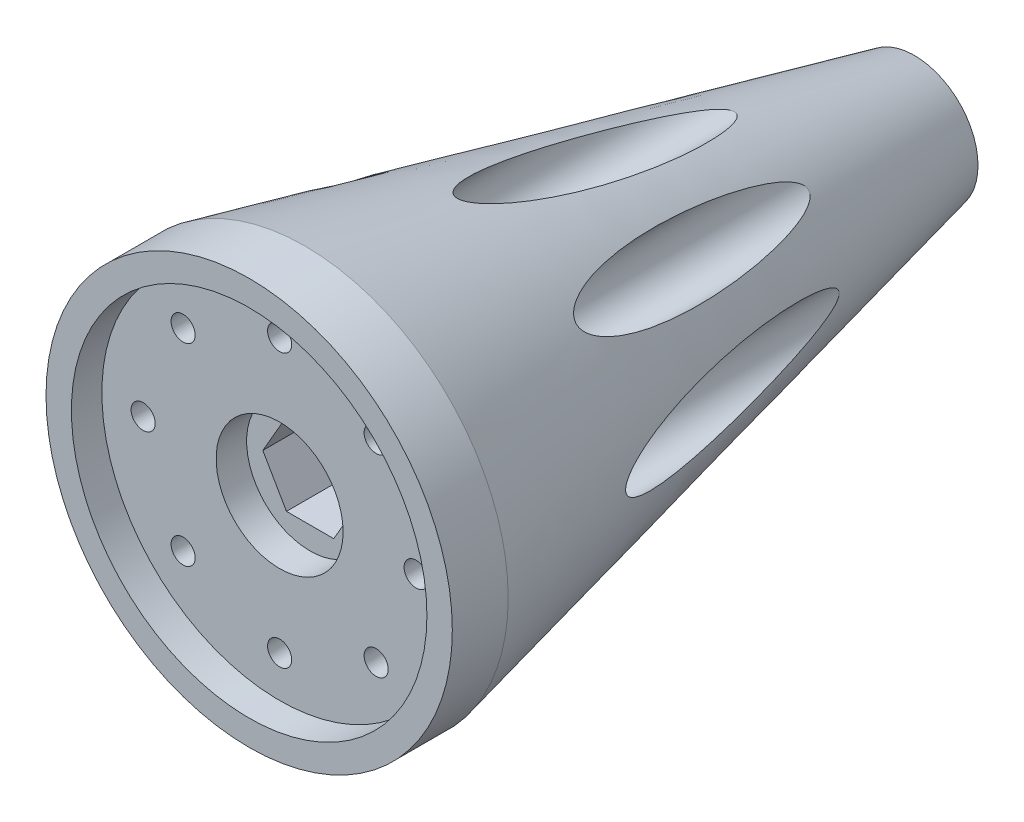
SolidWorks part; units mm, degrees
ref_plane "Front Plane" through (0, 0, 0) normal (0, 0, 1) x (1, 0, 0)
ref_plane "Top Plane" through (0, 0, 0) normal (0, 1, 0) x (1, 0, 0)
ref_plane "Right Plane" through (0, 0, 0) normal (1, 0, 0) x (0, 0, -1)
sketch "Sketch2" plane through (0, 0, 0) normal (1, 0, 0) x (0, 0, -1)
  line L0 (0, 0) -> (28.0138, 0) construction
  line L1 (0, 14) -> (2.4, 14)
  line L2 (2.4, 14) -> (2.4, 0)
  line L3 (2.4, 0) -> (52.4, 0)
  line L4 (52.4, 0) -> (52.4, 5)
  line L5 (52.4, 5) -> (4.4, 16)
  line L6 (4.4, 16) -> (0, 16)
  line L7 (0, 16) -> (0, 14)
  dimension "D1" = 28
  dimension "D2" = 2.4
  dimension "D3" = 2
  dimension "D4" = 2
  dimension "D5" = 10
  dimension "D6" = 50
revolve "Revolve1" add sketch "Sketch2" angle 360 about L0
sketch "Sketch3" plane through (0, 0, 0) normal (0, 0, 1) x (1, 0, 0)
  line L1 (3.7239, 0) -> (1.862, 3.225)
  line L2 (1.862, 3.225) -> (-1.862, 3.225)
  line L3 (-1.862, 3.225) -> (-3.7239, 0)
  line L4 (-3.7239, 0) -> (-1.862, -3.225)
  line L5 (-1.862, -3.225) -> (1.862, -3.225)
  line L6 (1.862, -3.225) -> (3.7239, 0)
  circle A0 centre (0, 0) radius 3.225 construction
  dimension "D1" = 6.45
extrude "Cut-Extrude1" cut sketch "Sketch3" against normal up to next
sketch "Sketch4" plane through (0, 0, 0) normal (0, 0, 1) x (1, 0, 0)
  circle A0 centre (0, 0) radius 10.75 construction
  circle A1 centre (0, 10.75) radius 0.95
  circle A2 centre (7.6014, 7.6014) radius 0.95
  circle A3 centre (10.75, 0) radius 0.95
  circle A4 centre (7.6014, -7.6014) radius 0.95
  circle A5 centre (0, -10.75) radius 0.95
  circle A6 centre (-7.6014, -7.6014) radius 0.95
  circle A7 centre (-10.75, 0) radius 0.95
  circle A8 centre (-7.6014, 7.6014) radius 0.95
  point P22 (0, 0)
  dimension "D1" = 1.9
  dimension "D2" = 21.5
  dimension "D3" = 8
extrude "Cut-Extrude2" cut sketch "Sketch4" against normal up to next
sketch "Sketch5" plane through (0, 0, -52.4) normal (0, 0, -1) x (-1, 0, 0)
  circle A2 centre (0, 10.75) radius 2.5
  circle A3 centre (0, 10.75) radius 0.95 construction
  circle A4 centre (7.6014, 7.6014) radius 2.5
  circle A5 centre (10.75, 0) radius 2.5
  circle A6 centre (7.6014, -7.6014) radius 2.5
  circle A7 centre (0, -10.75) radius 2.5
  circle A8 centre (-7.6014, -7.6014) radius 2.5
  circle A9 centre (-10.75, 0) radius 2.5
  circle A10 centre (-7.6014, 7.6014) radius 2.5
  circle A11 centre (10.75, 0) radius 0.95 construction
  point P23 (0, 0)
  dimension "D1" = 5
  dimension "D2" = 8
extrude "Cut-Extrude3" cut sketch "Sketch5" against normal offset from surface (47 mm away) 3 up to face at (-0.95, 10.75, -2.4)
sketch "Sketch6" plane through (0, 0, -2.4) normal (0, 0, 1) x (1, 0, 0)
  circle A0 centre (0, 0) radius 5
  dimension "D1" = 10
extrude "Cut-Extrude4" cut sketch "Sketch6" against normal blind 2.4
